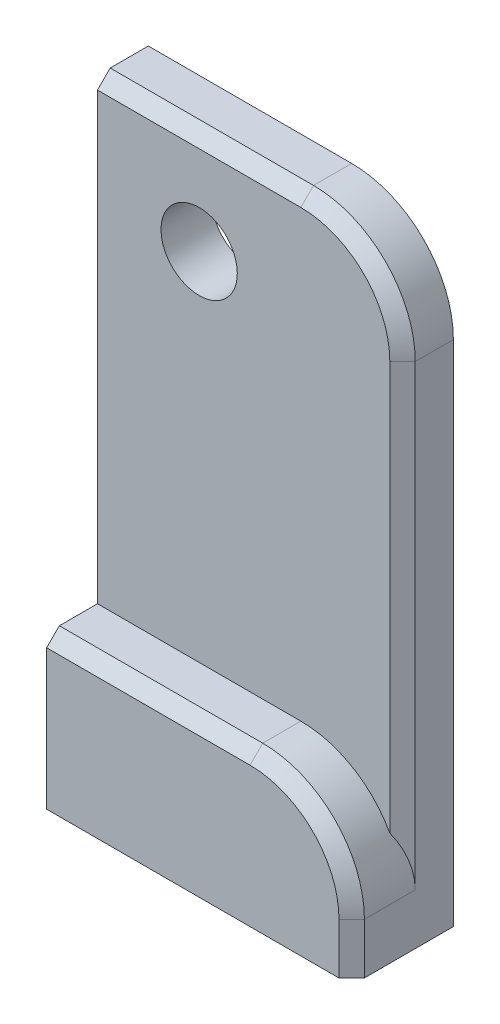
SolidWorks part; units mm, degrees
ref_plane "Front Plane" through (0, 0, 0) normal (0, 0, 1) x (1, 0, 0)
ref_plane "Top Plane" through (0, 0, 0) normal (0, 1, 0) x (1, 0, 0)
ref_plane "Right Plane" through (0, 0, 0) normal (1, 0, 0) x (0, 0, -1)
sketch "Sketch1" plane through (0, 0, 0) normal (0, 0, 1) x (1, 0, 0)
  line L1 (0, 0) -> (76.2, 0)
  line L2 (0, 0) -> (0, 152.4)
  line L3 (0, 152.4) -> (76.2, 152.4)
  line L4 (76.2, 0) -> (76.2, 152.4)
  dimension "D1" = 76.2
  dimension "D2" = 152.4
extrude "Boss-Extrude1" add sketch "Sketch1" along normal blind 12.7 contours L2 L1 L4 L3
sketch "Sketch2" plane through (0, 0, 12.7) normal (0, 0, 1) x (1, 0, 0)
  line L0 (76.2, 0) -> (76.2, 152.4) construction
  line L1 (0, 0) -> (76.2, 0)
  line L2 (0, 0) -> (0, 38.1)
  line L3 (0, 38.1) -> (76.2, 38.1)
  line L4 (76.2, 0) -> (76.2, 38.1)
  dimension "D1" = 38.1
extrude "Boss-Extrude2" add sketch "Sketch2" along normal blind 12.7
sketch "Sketch3" plane through (0, 0, 12.7) normal (0, 0, 1) x (1, 0, 0)
  line L0 (0, 152.4) -> (76.2, 152.4) construction
  line L1 (0, 38.1) -> (0, 152.4) construction
  circle A0 centre (25.4, 127) radius 9.525
  dimension "D1" = 19.05
  dimension "D2" = 25.4
  dimension "D3" = 25.4
extrude "Cut-Extrude1" cut sketch "Sketch3" against normal through all
fillet "Fillet1" radius 25.4 2 edges at (76.2, 38.1, 19.05) (76.2, 152.4, 6.35)
chamfer "Chamfer1" distance 3.175 angle 45 6 edges at (76.2, 6.35, 25.4) (68.7605, 30.6605, 25.4) (25.4, 38.1, 25.4) (76.2, 69.85, 12.7) (68.7605, 144.9605, 12.7) (25.4, 152.4, 12.7)
shell "Shell1" thickness 2.54
